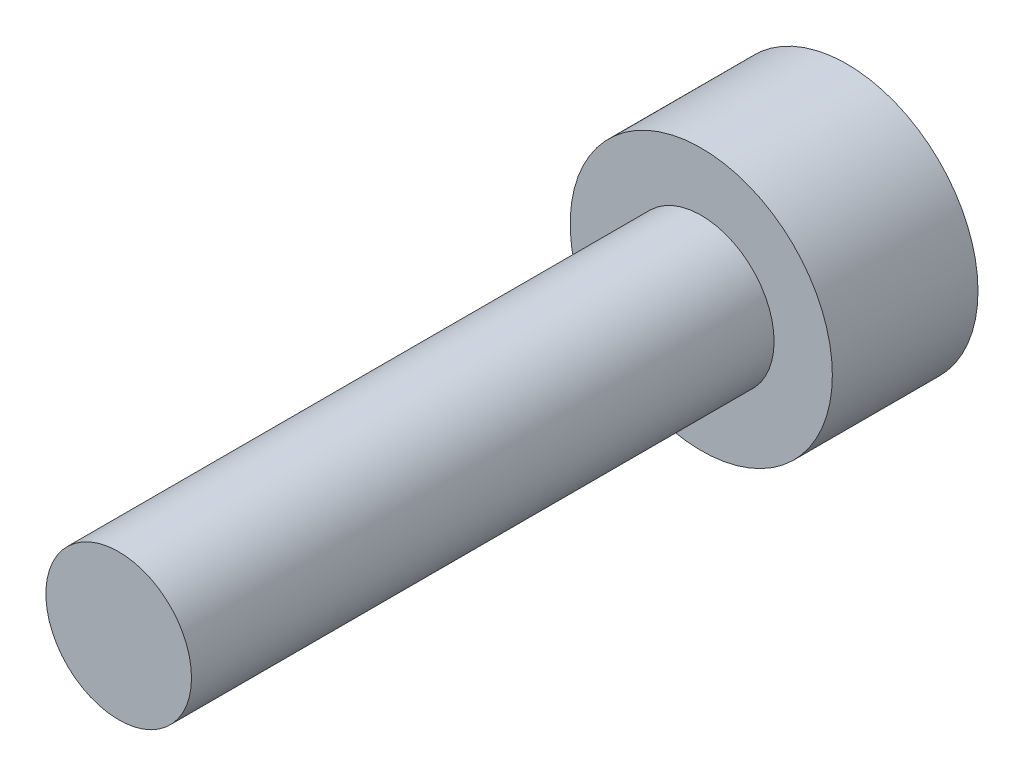
SolidWorks part; units mm, degrees
material "AISI 304"
ref_plane "Alzado" through (0, 0, 0) normal (0, 0, 1) x (1, 0, 0)
ref_plane "Planta" through (0, 0, 0) normal (0, 1, 0) x (1, 0, 0)
ref_plane "Vista lateral" through (0, 0, 0) normal (1, 0, 0) x (0, 0, -1)
sketch "Sk_Cabeza" plane through (0, 0, 0) normal (0, 0, 1) x (1, 0, 0)
  circle A0 centre (0, 0) radius 2.25
  dimension "D1" = 4.5
extrude "Cabeza" add sketch "Sk_Cabeza" along normal blind 2.5 from offset 2.5
sketch "Sk_Cuerpo" plane through (0, 0, 0) normal (0, 0, 1) x (1, 0, 0)
  circle A0 centre (0, 0) radius 1.25
  dimension "D1" = 2.5
extrude "Cuerpo" add sketch "Sk_Cuerpo" along normal blind 10
sketch "Sk_Hexagono_interior" plane through (0, 0, 0) normal (0, 0, 1) x (1, 0, 0)
  line L1 (0, -1.1547) -> (1, -0.5774)
  line L2 (1, -0.5774) -> (1, 0.5774)
  line L3 (1, 0.5774) -> (0, 1.1547)
  line L4 (0, 1.1547) -> (-1, 0.5774)
  line L5 (-1, 0.5774) -> (-1, -0.5774)
  line L6 (-1, -0.5774) -> (0, -1.1547)
  circle A0 centre (0, 0) radius 1 construction
  dimension "D1" = 2
extrude "Hexagono_interior" cut sketch "Sk_Hexagono_interior" along normal blind 1.25 from offset 2.5
